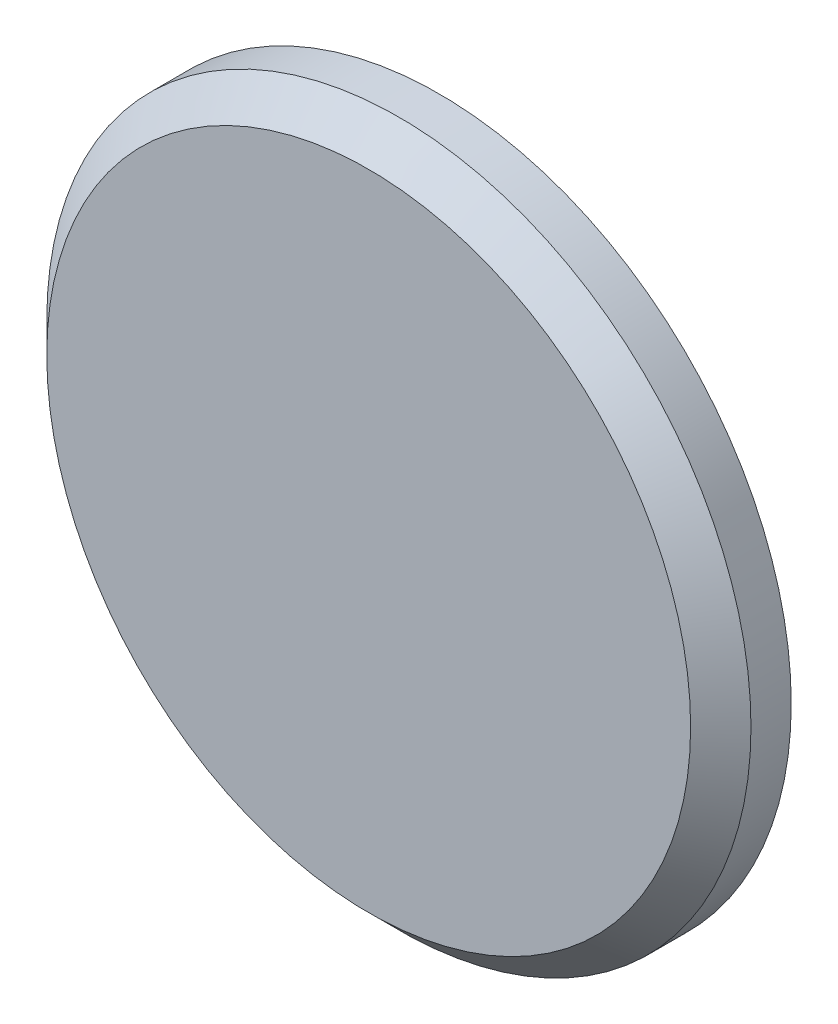
SolidWorks part; units mm, degrees
material "Q235A"
ref_plane "前视" through (0, 0, 0) normal (0, 0, 1) x (1, 0, 0)
ref_plane "上视" through (0, 0, 0) normal (0, 1, 0) x (1, 0, 0)
ref_plane "右视" through (0, 0, 0) normal (1, 0, 0) x (0, 0, -1)
sketch "草图1" plane through (0, 0, 0) normal (0, 0, 1) x (1, 0, 0)
  circle A0 centre (0, 0) radius 35
  dimension "D1" = 70
extrude "凸台-拉伸1" add sketch "草图1" along normal blind 7
chamfer "倒角1" distance 3 angle 45 1 edges at (35, 0, 7)
